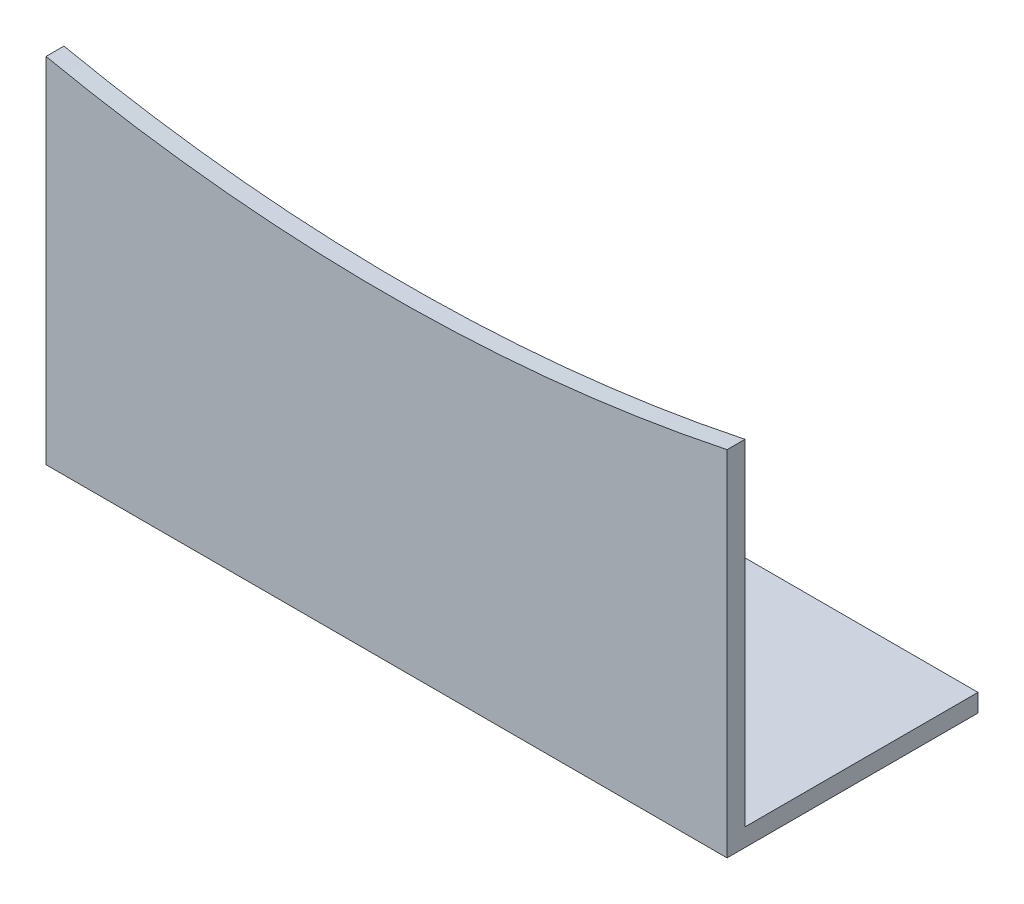
SolidWorks part; units mm, degrees
ref_plane "Plano frontal" through (0, 0, 0) normal (0, 0, 1) x (1, 0, 0)
ref_plane "Plano superior" through (0, 0, 0) normal (0, 1, 0) x (1, 0, 0)
ref_plane "Plano direito" through (0, 0, 0) normal (1, 0, 0) x (0, 0, -1)
sketch "Sketch1" plane through (0, 0, 0) normal (0, 0, 1) x (1, 0, 0)
  line L0 (38, -220) -> (38, -180.5443) construction
  line L1 (-38, -180.5443) -> (-38, -220) construction
  line L2 (38, -220) -> (38, -180.5443)
  line L3 (-38, -180.5443) -> (-38, -220)
  line L4 (-38, -220) -> (38, -220)
  arc A0 (-38, -180.5443) -> (38, -180.5443) centre (0, 0) ccw construction
  arc A1 (-38, -180.5443) -> (38, -180.5443) centre (0, 0) ccw
extrude "Boss-Extrude1" add sketch "Sketch1" against normal up to body (28 mm away) separate body
shell "Shell1" thickness 2
